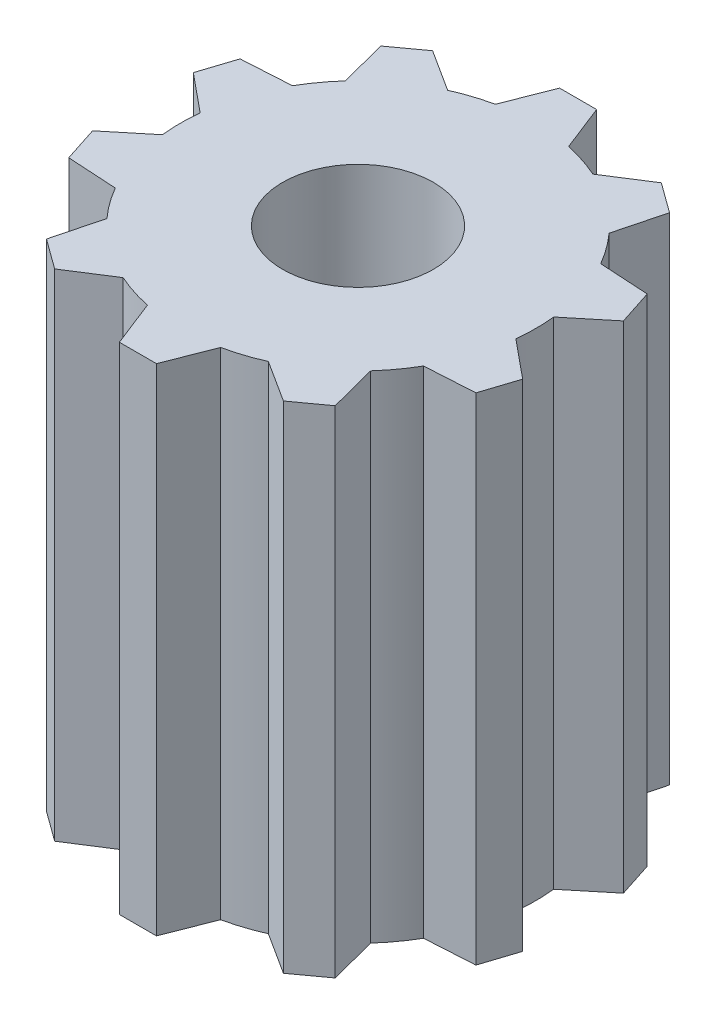
SolidWorks part; units mm, degrees
ref_plane "Front Plane" through (0, 0, 0) normal (0, 0, 1) x (1, 0, 0)
ref_plane "Top Plane" through (0, 0, 0) normal (0, 1, 0) x (1, 0, 0)
ref_plane "Right Plane" through (0, 0, 0) normal (1, 0, 0) x (0, 0, -1)
sketch "Sketch1" plane through (0, 0, 0) normal (0, 1, 0) x (1, 0, 0)
  circle A0 centre (0, 0) radius 3.5
extrude "Boss-Extrude1" add sketch "Sketch1" along normal blind 5
sketch "Sketch2" plane through (0, 5, 0) normal (0, 1, 0) x (1, 0, 0)
  circle A0 centre (0, 0) radius 3.5
ref_plane "Plane2" through (0, 5, 0) normal (0, -1, 0) x (-1, 0, 0)
sketch "Sketch12" plane through (0, 5, 0) normal (0, -1, 0) x (-1, 0, 0)
  circle A0 centre (0, 0) radius 3.5 construction
  circle A2 centre (0, 0) radius 12.25 construction
  circle A3 centre (0, 0) radius 8.25
  circle A4 centre (0, 0) radius 10.25 construction
  circle A5 centre (0, 0) radius 3.5
  dimension "D1" = 16.5
  dimension "D2" = 20.5
  dimension "D3" = 24.5
extrude "Boss-Extrude6" add sketch "Sketch12" along normal blind 5 separate body
sketch "Sketch13" plane through (0, 0, 0) normal (0, -1, 0) x (1, 0, 0)
  line L0 (0, 12.25) -> (0, -12.25) construction
  line L1 (-12.25, 0) -> (12.25, 0) construction
  line L2 (0.86, 10.2139) -> (1.7, 8.0729)
  line L3 (-0.86, 10.2139) -> (-1.7, 8.0729)
  line L4 (-0.86, 10.2139) -> (0.86, 10.2139)
  line L5 (-1.7, 8.0729) -> (3.0326, 8.2556) construction
  circle A0 centre (0, 0) radius 10.25 construction
  circle A1 centre (0, 0) radius 12.25 construction
  circle A3 centre (0, 0) radius 8.25 construction
  circle A4 centre (0, 0) radius 8.25
  circle A5 centre (0, 0) radius 8.25
  circle A6 centre (0, 0) radius 8.25
  point P11 (0, 0)
  circle M1 centre (0, 0) radius 8.25
  dimension "D1" = 20.5
  dimension "D2" = 24.5
  dimension "D3" = 16.5
  dimension "D4" = 1.7
  dimension "D5" = 1.7
  dimension "D6" = 1.72
  dimension "D7" = 66.367
  dimension "D8" = 0
extrude "Boss-Extrude9" add sketch "Sketch13" against normal blind 5 separate body contours L4 L3 L2 M1
pattern_circular "CirPattern2" count 10 over 360 about axis through (0, 0, 0) along (0, 1, 0) of bodies 130
sketch "Sketch14" plane through (0, 5, 0) normal (0, 1, 0) x (1, 0, 0)
  circle A0 centre (0, 0) radius 3.5 construction
  circle A1 centre (0, 0) radius 3.5
extrude "Cut-Extrude1" cut sketch "Sketch14" against normal blind 10
sketch "Sketch17" plane through (0, 0, 0) normal (0, -1, 0) x (1, 0, 0)
  line L0 (9.4482, -3.9742) -> (9.9797, -2.3383) construction
  line L1 (9.9797, -2.3383) -> (8.2032, -0.8779) construction
  line L2 (7.1525, -4.1115) -> (9.4482, -3.9742) construction
  line L3 (5.3078, -8.7687) -> (6.6993, -7.7577) construction
  line L4 (6.6993, -7.7577) -> (6.1205, -5.5319) construction
  line L5 (3.3698, -7.5304) -> (5.3078, -8.7687) construction
  line L6 (-0.86, -10.2139) -> (0.86, -10.2139) construction
  line L7 (0.86, -10.2139) -> (1.7, -8.0729) construction
  line L8 (-1.7, -8.0729) -> (-0.86, -10.2139) construction
  line L9 (-6.6993, -7.7577) -> (-5.3078, -8.7687) construction
  line L10 (-5.3078, -8.7687) -> (-3.3698, -7.5304) construction
  line L11 (-6.1205, -5.5319) -> (-6.6993, -7.7577) construction
  line L12 (-9.9797, -2.3383) -> (-9.4482, -3.9742) construction
  line L13 (-9.4482, -3.9742) -> (-7.1525, -4.1115) construction
  line L14 (-8.2032, -0.8779) -> (-9.9797, -2.3383) construction
  line L15 (-5.3078, 8.7687) -> (-6.6993, 7.7577) construction
  line L16 (-6.6993, 7.7577) -> (-6.1205, 5.5319) construction
  line L17 (-3.3698, 7.5304) -> (-5.3078, 8.7687) construction
  line L18 (-9.4482, 3.9742) -> (-9.9797, 2.3383) construction
  line L19 (-9.9797, 2.3383) -> (-8.2032, 0.8779) construction
  line L20 (-7.1525, 4.1115) -> (-9.4482, 3.9742) construction
  line L21 (9.9797, 2.3383) -> (9.4482, 3.9742) construction
  line L22 (9.4482, 3.9742) -> (7.1525, 4.1115) construction
  line L23 (8.2032, 0.8779) -> (9.9797, 2.3383) construction
  line L24 (6.6993, 7.7577) -> (5.3078, 8.7687) construction
  line L25 (5.3078, 8.7687) -> (3.3698, 7.5304) construction
  line L26 (6.1205, 5.5319) -> (6.6993, 7.7577) construction
  line L27 (0.86, 10.2139) -> (-0.86, 10.2139) construction
  line L28 (-0.86, 10.2139) -> (-1.7, 8.0729) construction
  line L29 (1.7, 8.0729) -> (0.86, 10.2139) construction
  line L30 (9.4482, -3.9742) -> (9.9797, -2.3383)
  line L31 (9.9797, -2.3383) -> (8.2032, -0.8779)
  line L32 (7.1525, -4.1115) -> (9.4482, -3.9742)
  line L33 (5.3078, -8.7687) -> (6.6993, -7.7577)
  line L34 (6.6993, -7.7577) -> (6.1205, -5.5319)
  line L35 (3.3698, -7.5304) -> (5.3078, -8.7687)
  line L36 (-0.86, -10.2139) -> (0.86, -10.2139)
  line L37 (0.86, -10.2139) -> (1.7, -8.0729)
  line L38 (-1.7, -8.0729) -> (-0.86, -10.2139)
  line L39 (-6.6993, -7.7577) -> (-5.3078, -8.7687)
  line L40 (-5.3078, -8.7687) -> (-3.3698, -7.5304)
  line L41 (-6.1205, -5.5319) -> (-6.6993, -7.7577)
  line L42 (-9.9797, -2.3383) -> (-9.4482, -3.9742)
  line L43 (-9.4482, -3.9742) -> (-7.1525, -4.1115)
  line L44 (-8.2032, -0.8779) -> (-9.9797, -2.3383)
  line L45 (-5.3078, 8.7687) -> (-6.6993, 7.7577)
  line L46 (-6.6993, 7.7577) -> (-6.1205, 5.5319)
  line L47 (-3.3698, 7.5304) -> (-5.3078, 8.7687)
  line L48 (-9.4482, 3.9742) -> (-9.9797, 2.3383)
  line L49 (-9.9797, 2.3383) -> (-8.2032, 0.8779)
  line L50 (-7.1525, 4.1115) -> (-9.4482, 3.9742)
  line L51 (9.9797, 2.3383) -> (9.4482, 3.9742)
  line L52 (9.4482, 3.9742) -> (7.1525, 4.1115)
  line L53 (8.2032, 0.8779) -> (9.9797, 2.3383)
  line L54 (6.6993, 7.7577) -> (5.3078, 8.7687)
  line L55 (5.3078, 8.7687) -> (3.3698, 7.5304)
  line L56 (6.1205, 5.5319) -> (6.6993, 7.7577)
  line L57 (0.86, 10.2139) -> (-0.86, 10.2139)
  line L58 (-0.86, 10.2139) -> (-1.7, 8.0729)
  line L59 (1.7, 8.0729) -> (0.86, 10.2139)
  arc A0 (7.1525, -4.1115) -> (8.2032, -0.8779) centre (0, 0) ccw construction
  arc A1 (3.3698, -7.5304) -> (6.1205, -5.5319) centre (0, 0) ccw construction
  arc A2 (-1.7, -8.0729) -> (1.7, -8.0729) centre (0, 0) ccw construction
  arc A4 (-6.1205, -5.5319) -> (-3.3698, -7.5304) centre (0, 0) ccw construction
  arc A5 (-8.2032, -0.8779) -> (-7.1525, -4.1115) centre (0, 0) ccw construction
  arc A6 (-3.3698, 7.5304) -> (-6.1205, 5.5319) centre (0, 0) ccw construction
  arc A7 (-7.1525, 4.1115) -> (-8.2032, 0.8779) centre (0, 0) ccw construction
  arc A8 (8.2032, 0.8779) -> (7.1525, 4.1115) centre (0, 0) ccw construction
  arc A9 (6.1205, 5.5319) -> (3.3698, 7.5304) centre (0, 0) ccw construction
  arc A10 (1.7, 8.0729) -> (-1.7, 8.0729) centre (0, 0) ccw construction
  circle A11 centre (0, 0) radius 8.25 construction
  arc A12 (7.1525, -4.1115) -> (8.2032, -0.8779) centre (0, 0) ccw
  arc A13 (3.3698, -7.5304) -> (6.1205, -5.5319) centre (0, 0) ccw
  arc A14 (-1.7, -8.0729) -> (1.7, -8.0729) centre (0, 0) ccw
  arc A15 (-6.1205, -5.5319) -> (-3.3698, -7.5304) centre (0, 0) ccw
  arc A16 (-8.2032, -0.8779) -> (-7.1525, -4.1115) centre (0, 0) ccw
  arc A17 (-3.3698, 7.5304) -> (-6.1205, 5.5319) centre (0, 0) ccw
  arc A18 (-7.1525, 4.1115) -> (-8.2032, 0.8779) centre (0, 0) ccw
  arc A19 (8.2032, 0.8779) -> (7.1525, 4.1115) centre (0, 0) ccw
  arc A20 (6.1205, 5.5319) -> (3.3698, 7.5304) centre (0, 0) ccw
  arc A21 (1.7, 8.0729) -> (-1.7, 8.0729) centre (0, 0) ccw
  circle A22 centre (0, 0) radius 8.25
  circle M1 centre (0, 0) radius 8.25
  circle M2 centre (0, 0) radius 3.5
other "AlignGroup1"
other "AlignGroup2"
extrude "Boss-Extrude10" add sketch "Sketch17" along normal blind 18 contours M1 M2 | L59 L57 L58 M1 | L47 L45 L46 M1 | L50 L48 L49 M1 | L44 L42 L43 M1 | L41 L39 L40 M1 | L38 L36 L37 M1 | L35 L33 L34 M1 | L32 L30 L31 M1 | L53 L51 L52 M1 | L56 L54 L55 M1
